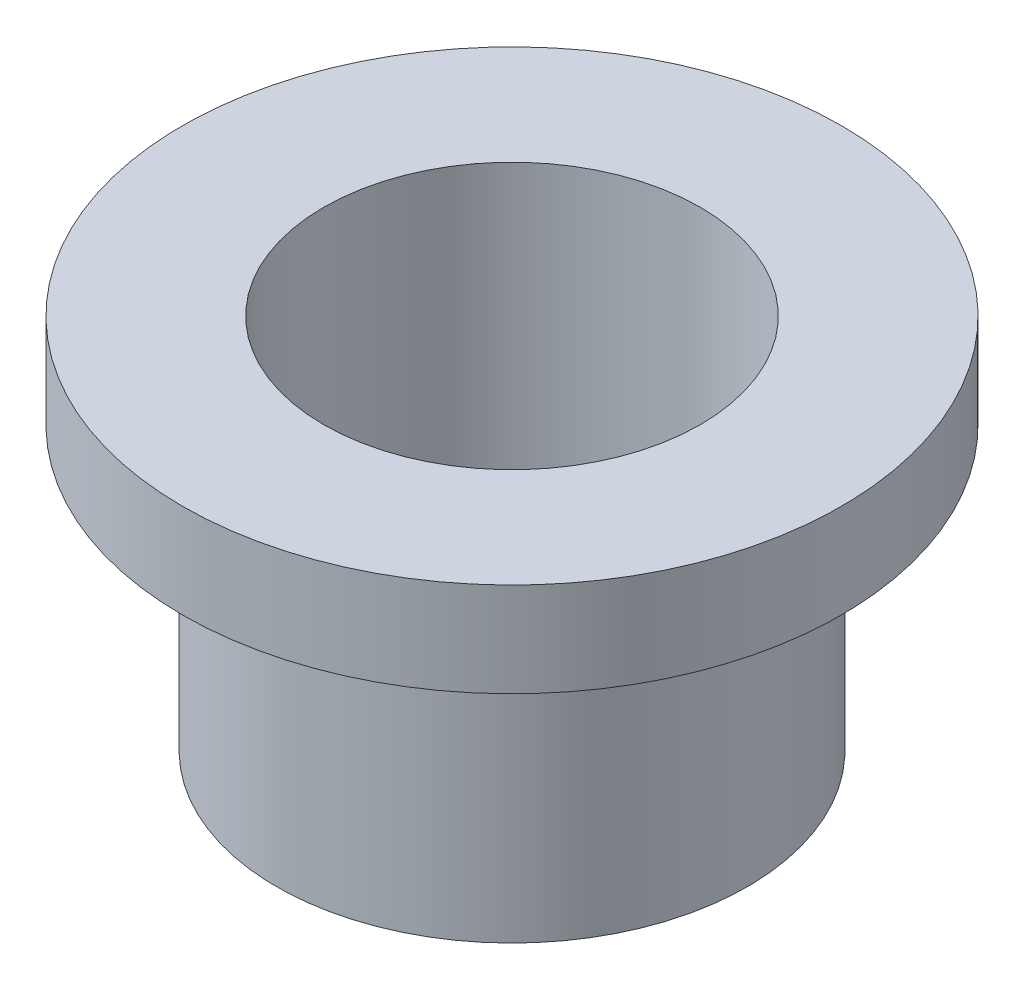
SolidWorks part; units mm, degrees
material "Tin Bearing Bronze"
ref_plane "Front Plane" through (0, 0, 0) normal (0, 0, 1) x (1, 0, 0)
ref_plane "Top Plane" through (0, 0, 0) normal (0, 1, 0) x (1, 0, 0)
ref_plane "Right Plane" through (0, 0, 0) normal (1, 0, 0) x (0, 0, -1)
sketch "Sketch1" plane through (0, 0, 0) normal (0, 1, 0) x (1, 0, 0)
  circle A0 centre (0, 0) radius 7.9375
  circle A1 centre (0, 0) radius 6.35
  dimension "D1" = 12.7
  dimension "D2" = 15.875
extrude "Boss-Extrude1" add sketch "Sketch1" along normal blind 9.525
sketch "Sketch2" plane through (0, 9.525, 0) normal (0, 1, 0) x (1, 0, 0)
  circle A0 centre (0, 0) radius 6.35
  circle A1 centre (0, 0) radius 6.35 construction
  circle A2 centre (0, 0) radius 11.1125
  dimension "D1" = 22.225
extrude "Boss-Extrude2" add sketch "Sketch2" along normal blind 3.175
